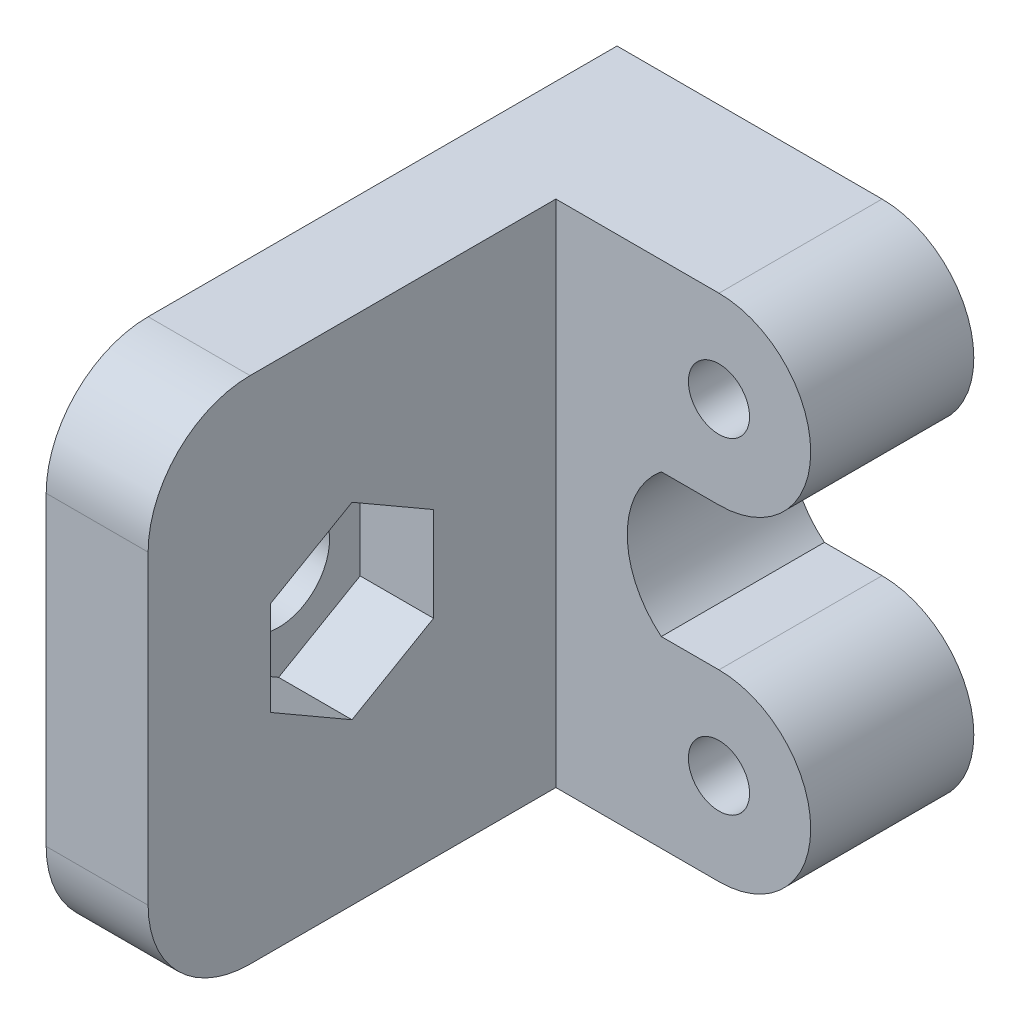
SolidWorks part; units mm, degrees
ref_plane "Alzado" through (0, 0, 0) normal (0, 0, 1) x (1, 0, 0)
ref_plane "Planta" through (0, 0, 0) normal (0, 1, 0) x (1, 0, 0)
ref_plane "Vista lateral" through (0, 0, 0) normal (1, 0, 0) x (0, 0, -1)
sketch "Croquis1" plane through (0, 0, 0) normal (0, 0, 1) x (1, 0, 0)
  line L0 (0, 0) -> (0, 16) construction
  line L1 (-13, 20.5) -> (0, 20.5)
  line L3 (-13, -4.5) -> (-13, 20.5)
  line L6 (-13, -4.5) -> (0, -4.5)
  line L7 (-13, 8) -> (0, 8) construction
  line L8 (0, 11.5) -> (-2.8284, 11.5)
  line L9 (0, 4.5) -> (-2.8284, 4.5)
  circle A0 centre (0, 0) radius 1.5
  circle A1 centre (0, 16) radius 1.5
  arc A2 (0, -4.5) -> (0, 4.5) centre (0, 0) ccw
  arc A3 (0, 11.5) -> (0, 20.5) centre (0, 16) ccw
  arc A4 (-2.8284, 11.5) -> (-2.8284, 4.5) centre (0, 8) ccw
  point P3 (-5.5321, 20.5)
  dimension "D1" = 3
  dimension "D3" = 3
  dimension "D2" = 16
  dimension "D4" = 13
  dimension "D5" = 13
extrude "Saliente-Extruir1" add sketch "Croquis1" along normal blind 8
sketch "Croquis2" plane through (0, 0, 8) normal (0, 0, 1) x (1, 0, 0)
  line L1 (-13, -4.5) -> (-8, -4.5)
  line L2 (-13, -4.5) -> (-13, 20.5)
  line L3 (-13, 20.5) -> (-8, 20.5)
  line L4 (-8, -4.5) -> (-8, 20.5)
  line L5 (-13, -4.5) -> (0, -4.5) construction
  point P5 (0, 0)
  point P9 (0, 0)
  dimension "D1" = 5
extrude "Saliente-Extruir2" add sketch "Croquis2" along normal blind 20
sketch "Croquis3" plane through (-8, 0, 0) normal (1, 0, 0) x (0, 0, -1)
  line L0 (-28, 20.5) -> (-8, -4.5) construction
  line L1 (-28, -4.5) -> (-8, -4.5) construction
  line L2 (-8, 4.5) -> (-8, -4.5) construction
  circle A0 centre (-18, 8) radius 2.5
  point P6 (0, 0)
  point P7 (0, 0)
  point P9 (-12.1663, -2.3161)
  point P11 (0, 0)
  point P14 (0, 0)
  dimension "D1" = 5
extrude "Cortar-Extruir1" cut sketch "Croquis3" against normal blind 20
sketch "Croquis4" plane through (-8, 0, 0) normal (1, 0, 0) x (0, 0, -1)
  line L0 (-18, 3.3812) -> (-18, -4.5) construction
  line L1 (-18, 3.3812) -> (-14, 5.6906)
  line L2 (-14, 5.6906) -> (-14, 10.3094)
  line L3 (-14, 10.3094) -> (-18, 12.6188)
  line L4 (-18, 12.6188) -> (-22, 10.3094)
  line L5 (-22, 10.3094) -> (-22, 5.6906)
  line L6 (-22, 5.6906) -> (-18, 3.3812)
  line L7 (-28, -4.5) -> (-8, -4.5) construction
  circle A0 centre (-18, 8) radius 4 construction
  dimension "D1" = 8
extrude "Cortar-Extruir2" cut sketch "Croquis4" against normal blind 3.6
fillet "Redondeo1" radius 5 2 edges at (-10.5, -4.5, 28) (-10.5, 20.5, 28)
